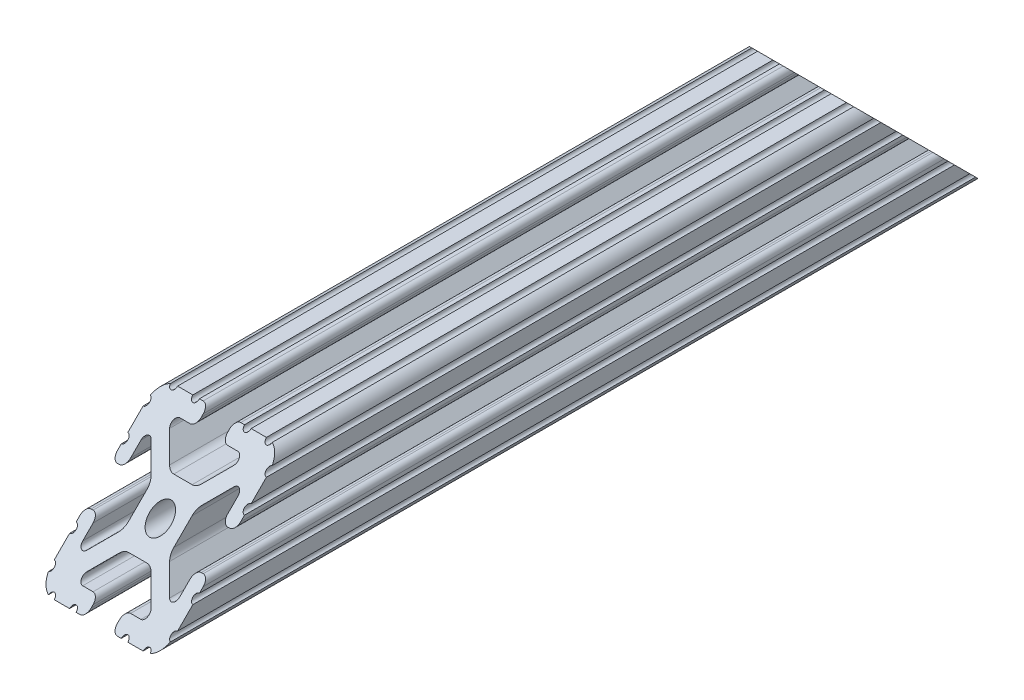
SolidWorks part; units mm, degrees
ref_plane "Front Plane" through (0, 0, 0) normal (0, 0, 1) x (1, 0, 0)
ref_plane "Top Plane" through (0, 0, 0) normal (0, 1, 0) x (1, 0, 0)
ref_plane "Right Plane" through (0, 0, 0) normal (1, 0, 0) x (0, 0, -1)
sketch "Sketch2" plane through (0, 0, 0) normal (0, 0, 1) x (1, 0, 0)
  line L0 (0, 19.05) -> (0, -19.05) construction
  line L1 (-19.05, 0) -> (19.05, 0) construction
  line L2 (4.064, -19.05) -> (19.05, -19.05)
  line L3 (19.05, -19.05) -> (19.05, -4.064)
  line L4 (4.064, -19.05) -> (4.064, -14.986)
  line L5 (4.064, -14.986) -> (12.1123, -14.986)
  line L6 (12.1123, -14.986) -> (4.1113, -6.985)
  line L7 (0, 0) -> (19.05, -19.05) construction
  line L8 (19.05, -4.064) -> (14.986, -4.064)
  line L9 (14.986, -4.064) -> (14.986, -12.1123)
  line L10 (14.986, -12.1123) -> (6.985, -4.1113)
  circle A0 centre (0, 0) radius 3.3274
  arc A1 (8.9963, -14.986) -> (9.909, -12.7826) centre (8.9963, -13.6953) ccw construction
  point P8 (0, -6.985)
  dimension "Center Hole Diameter" = 6.6548
  dimension "Rail Height" = 38.1
  dimension "Rail Width" = 38.1
  dimension "T-Slot Width" = 8.128
  dimension "Slot Inner Width" = 20.574
  dimension "Thickness" = 4.064
  dimension "Slot Depth" = 8.001
  dimension "D1" = 4.064
sketch "Sketch3" plane through (0, 0, 0) normal (1, 0, 0) x (0, 0, -1)
  line L0 (-304.8, -19.05) -> (304.8, -19.05) construction
  line L1 (-279.4, 0) -> (279.4, 0) construction
  dimension "Length" = 609.6
  dimension "D1" = 25.4
sketch "Sketch4" plane through (0, 0, 0) normal (0, 0, 1) x (1, 0, 0)
  line L0 (5.7912, -19.05) -> (14.3002, -19.05)
  line L1 (4.064, -19.05) -> (19.05, -19.05) construction
  line L2 (4.064, -19.05) -> (4.064, -14.986) construction
  line L3 (4.064, -14.986) -> (12.1123, -14.986) construction
  line L4 (4.064, -16.7132) -> (4.064, -17.3228)
  line L5 (5.7912, -14.986) -> (8.9963, -14.986)
  line L6 (0, -6.985) -> (2.833, -6.985)
  line L7 (12.1123, -14.986) -> (4.1113, -6.985) construction
  line L8 (5.0152, -7.8889) -> (9.909, -12.7826)
  line L9 (19.05, -19.05) -> (19.05, -4.064) construction
  line L10 (14.986, -12.1123) -> (6.985, -4.1113) construction
  line L11 (14.986, -4.064) -> (14.986, -12.1123) construction
  line L12 (14.986, -8.9963) -> (14.986, -5.7912)
  line L13 (19.05, -4.064) -> (14.986, -4.064) construction
  line L14 (16.7132, -4.064) -> (17.3228, -4.064)
  line L15 (19.05, -5.7912) -> (19.05, -14.3002)
  line L16 (12.7826, -9.909) -> (7.8889, -5.0152)
  line L17 (6.985, 0) -> (6.985, -2.833)
  line L18 (-19.05, 0) -> (19.05, 0) construction
  line L19 (0, -6.985) -> (0, -3.3274)
  line L20 (0, 19.05) -> (0, -19.05) construction
  line L21 (6.985, 0) -> (3.3274, 0)
  arc A0 (4.064, -17.3228) -> (5.7912, -19.05) centre (5.7912, -17.3228) ccw
  arc A2 (4.064, -16.7132) -> (5.7912, -14.986) centre (5.7912, -16.7132) cw
  arc A3 (8.9963, -14.986) -> (9.909, -12.7826) centre (8.9963, -13.6953) ccw
  arc A4 (2.833, -6.985) -> (5.0152, -7.8889) centre (2.833, -10.0711) cw
  arc A5 (14.3002, -19.05) -> (19.05, -14.3002) centre (14.3002, -14.3002) ccw
  arc A6 (12.7826, -9.909) -> (14.986, -8.9963) centre (13.6953, -8.9963) ccw
  arc A7 (14.986, -5.7912) -> (16.7132, -4.064) centre (16.7132, -5.7912) cw
  arc A8 (17.3228, -4.064) -> (19.05, -5.7912) centre (17.3228, -5.7912) cw
  arc A9 (7.8889, -5.0152) -> (6.985, -2.833) centre (10.0711, -2.833) cw
  circle A10 centre (0, 0) radius 3.3274 construction
  arc A11 (0, -3.3274) -> (3.3274, 0) centre (0, 0) ccw
  dimension "D1" = 4.7498
  dimension "D2" = 3.0861
  dimension "D3" = 1.7272
extrude "Boss-Extrude1" add sketch "Sketch4" along normal mid plane 609.6
sketch "Sketch5" plane through (0, 0, 0) normal (0, 0, 1) x (1, 0, 0)
  line L0 (4.064, -19.05) -> (19.05, -19.05) construction
  line L1 (5.7912, -14.986) -> (8.9963, -14.986) construction
  line L3 (0, 0) -> (19.05, -19.05) construction
  line L4 (8.9963, -14.986) -> (8.9963, -19.05) construction
  line L5 (12.1123, -14.986) -> (4.1113, -6.985) construction
  circle A0 centre (14.7395, -19.05) radius 1.016
  circle A1 centre (7.9803, -19.05) radius 1.016
  circle A2 centre (19.05, -14.7395) radius 1.016
  circle A3 centre (19.05, -7.9803) radius 1.016
  point P10 (7.3938, -14.986)
  point P12 (13.6953, -8.9963)
  dimension "D1" = 2.032
extrude "Cut-Extrude1" cut sketch "Sketch5" against normal through all both and the other way through all
mirror "Mirror1" about plane through (0, 0, 0) normal (1, 0, 0) of bodies 137 134
mirror "Mirror2" about plane through (0, 0, 0) normal (0, 1, 0) of bodies 135
sketch "Sketch6" plane through (0, 0, 0) normal (1, 0, 0) x (0, 0, -1)
  line L0 (-304.8, 19.05) -> (-304.8, -19.05)
  line L1 (-304.8, 19.05) -> (304.8, 19.05)
  line L2 (-304.8, -19.05) -> (304.8, -19.05)
  line L3 (304.8, 19.05) -> (304.8, -19.05)
  line L4 (-304.8, -19.05) -> (-266.7, 19.05)
  line L5 (-87.5363, 19.05) -> (-49.4363, -19.05)
  dimension "D1" = 45
  dimension "D2" = 45
  dimension "D3" = 179.1637
extrude "Cut-Extrude2" cut sketch "Sketch6" against normal through all both and the other way through all contours L0 L4 L1 | L1 L5 L2 L3
sketch "Sketch9" plane through (0, 0, 0) normal (1, 0, 0) x (0, 0, -1)
  line L0 (-285.8603, -0.1103) -> (-239.7983, -46.1724) construction
  line L1 (-266.9207, 18.8293) -> (-304.8, -19.05) construction
  line L2 (-285.8603, -0.1103) -> (-256.071, -29.8997)
  line L3 (-285.8603, -0.1103) -> (-283.5524, 2.1976)
  line L4 (-283.5524, 2.1976) -> (-279.0623, -2.2925)
  line L5 (-279.0623, -2.2925) -> (-275.7576, 1.0122)
  line L6 (-275.7576, 1.0122) -> (-250.4583, -24.287)
  line L7 (-250.4583, -24.287) -> (-256.071, -29.8997)
  dimension "D1" = 3.2639
  dimension "D2" = 6.35
  dimension "D3" = 7.9375
  dimension "D4" = 35.7785
equation "\"D1@Boss-Extrude1\"=\"Length@Sketch3\""
equation "\"D1@Sketch2\"=\"Thickness@Sketch2\""
equation "\"D2@Sketch4\"=\"Slot Inner Width@Sketch2\"*0.15"
equation "\"D1@Sketch4\"=\"D3@Sketch4\"*2.75"
equation "\"D3@Sketch4\"=\"Thickness@Sketch2\"*0.425"
equation "\"D1@Sketch5\"=\"Thickness@Sketch2\"*0.5"
